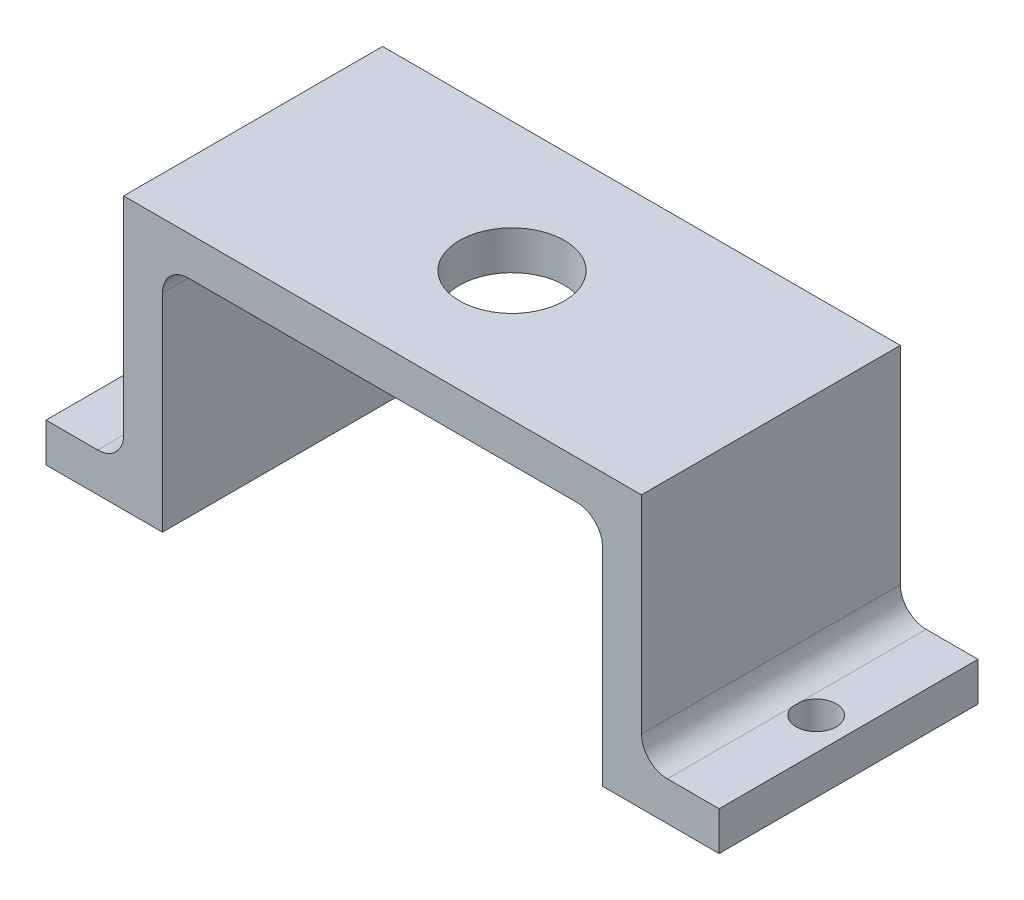
SolidWorks part; units mm, degrees
ref_plane "Front Plane" through (0, 0, 0) normal (0, 0, 1) x (1, 0, 0)
ref_plane "Top Plane" through (0, 0, 0) normal (0, 1, 0) x (1, 0, 0)
ref_plane "Right Plane" through (0, 0, 0) normal (1, 0, 0) x (0, 0, -1)
sketch "Sketch1" plane through (0, 0, 0) normal (0, 0, 1) x (1, 0, 0)
  line L0 (-17, -8.8641) -> (-26, -8.8641)
  line L1 (-26, -8.8641) -> (-26, -5.8641)
  line L2 (-26, -5.8641) -> (-20, -5.8641)
  line L3 (-20, -5.8641) -> (-20, 12.1359)
  line L4 (-20, 12.1359) -> (20, 12.1359)
  line L5 (20, 12.1359) -> (20, -5.8641)
  line L6 (20, -5.8641) -> (26, -5.8641)
  line L7 (26, -5.8641) -> (26, -8.8641)
  line L8 (26, -8.8641) -> (17, -8.8641)
  line L9 (17, -8.8641) -> (17, 9.1359)
  line L10 (17, 9.1359) -> (-17, 9.1359)
  line L11 (-17, 9.1359) -> (-17, -8.8641)
  dimension "D1" = 34
  dimension "D2" = 3
  dimension "D3" = 3
  dimension "D4" = 3
  dimension "D5" = 3
  dimension "D6" = 6
  dimension "D7" = 6
  dimension "D8" = 17
  dimension "D9" = 15
extrude "Boss-Extrude1" add sketch "Sketch1" along normal blind 20
sketch "Sketch2" plane through (0, 12.1359, 0) normal (0, 1, 0) x (1, 0, 0)
  circle A0 centre (0, -10) radius 4.05
  dimension "D1" = 8.1
extrude "Cut-Extrude1" cut sketch "Sketch2" against normal blind 16
fillet "Fillet1" radius 2 4 edges at (-17, 9.1359, 10) (17, 9.1359, 10) (20, -5.8641, 10) (-20, -5.8641, 10)
sketch "Sketch3" plane through (0, -5.8641, 0) normal (0, 1, 0) x (1, 0, 0)
  line L0 (-26, -20) -> (-26, 0) construction
  line L1 (26, -20) -> (26, 0) construction
  line L2 (26, 0) -> (22, 0) construction
  line L3 (-22, 0) -> (-26, 0) construction
  circle A0 centre (-23.5, -10) radius 1.55
  circle A1 centre (23.5, -10) radius 1.55
  point P4 (-26, -10)
  dimension "D1" = 3.1
  dimension "D2" = 2.5
  dimension "D3" = 2.5
  dimension "D4" = 10
  dimension "D5" = 10
extrude "Cut-Extrude2" cut sketch "Sketch3" against normal blind 16
